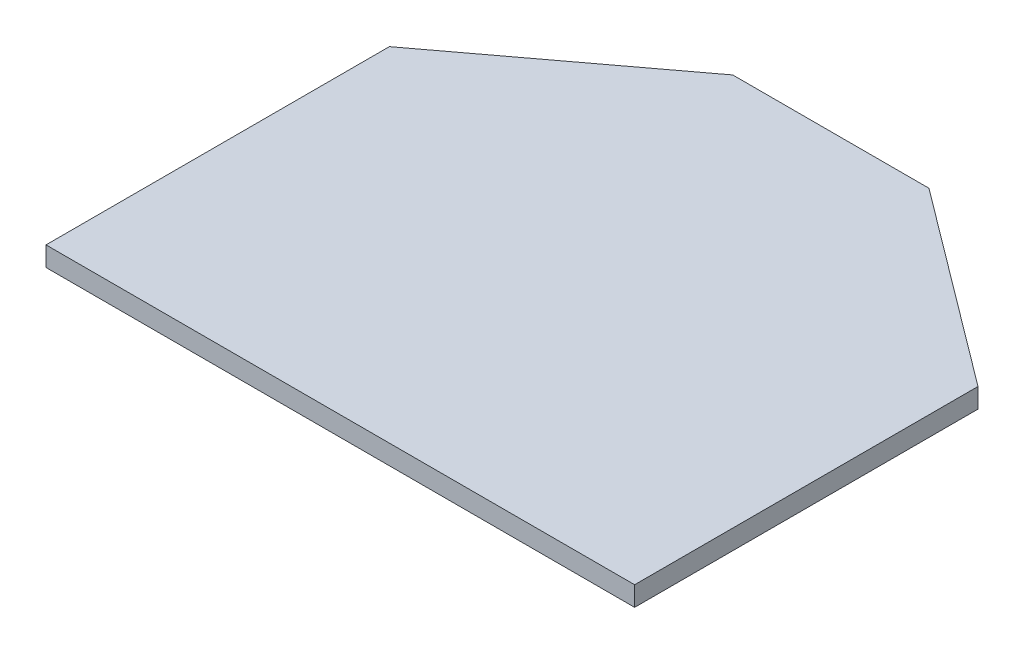
SolidWorks part; units mm, degrees
ref_plane "Front Plane" through (0, 0, 0) normal (0, 0, 1) x (1, 0, 0)
ref_plane "Top Plane" through (0, 0, 0) normal (0, 1, 0) x (1, 0, 0)
ref_plane "Right Plane" through (0, 0, 0) normal (1, 0, 0) x (0, 0, -1)
sketch "Sketch1" plane through (0, 0, 0) normal (0, 1, 0) x (1, 0, 0)
  line L0 (-90, 12.5) -> (-30, 57.5)
  line L1 (-90, -92.5) -> (90, -92.5)
  line L2 (-90, -92.5) -> (-90, 12.5)
  line L3 (-30, 57.5) -> (30, 57.5)
  line L4 (90, -92.5) -> (90, 12.5)
  line L5 (-90, -92.5) -> (45, 46.25) construction
  line L6 (-45, 46.25) -> (90, -92.5) construction
  line L7 (30, 57.5) -> (90, 12.5)
  point P0 (0, 0)
  point P1 (0, 0)
  point P12 (88.6808, 13.4894)
  dimension "D1" = 45
  dimension "D2" = 60
  dimension "D3" = 60
  dimension "D4" = 45
  dimension "D5" = 180
  dimension "D6" = 105
extrude "Boss-Extrude1" add sketch "Sketch1" along normal blind 6
